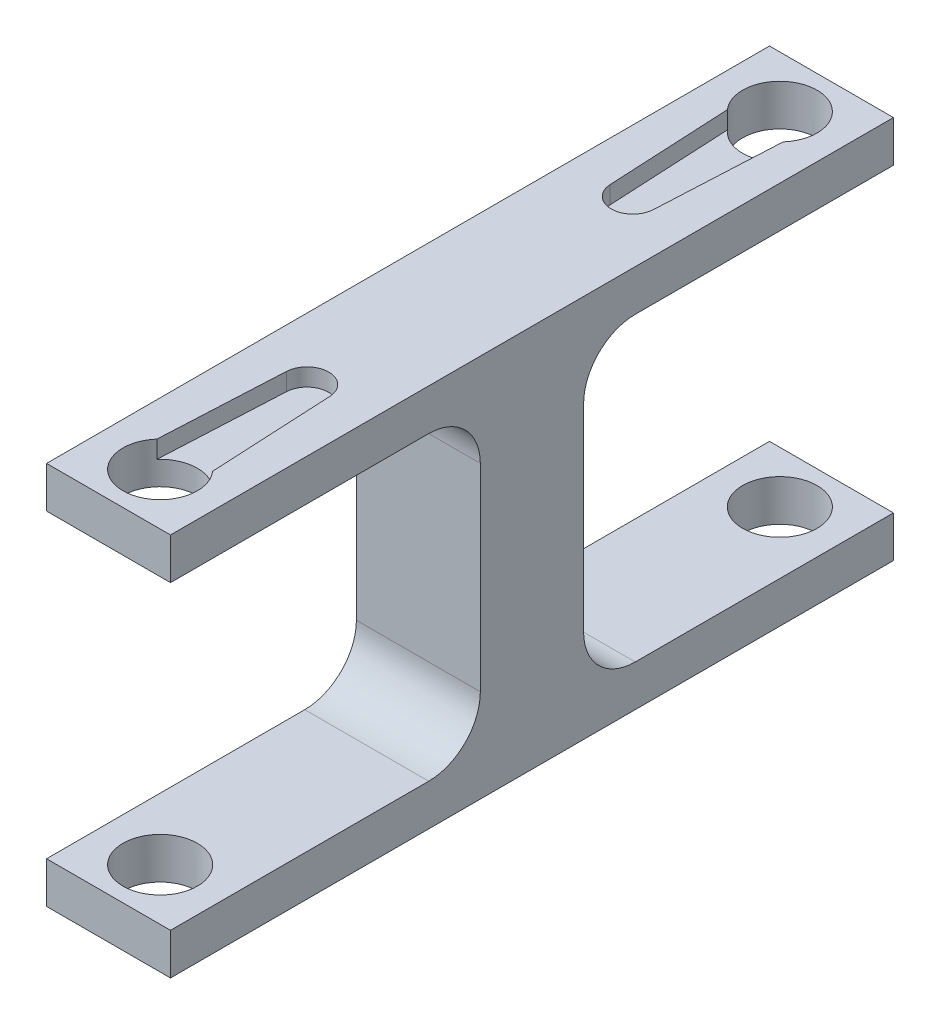
SolidWorks part; units mm, degrees
ref_plane "Front Plane" through (0, 0, 0) normal (0, 0, 1) x (1, 0, 0)
ref_plane "Top Plane" through (0, 0, 0) normal (0, 1, 0) x (1, 0, 0)
ref_plane "Right Plane" through (0, 0, 0) normal (1, 0, 0) x (0, 0, -1)
sketch "Sketch2" plane through (0, 0, 0) normal (0, 0, 1) x (1, 0, 0)
  line L1 (-8.6116, 0.9665) -> (3.3884, 0.9665)
  line L2 (-8.6116, 0.9665) -> (-8.6116, -36.1835)
  line L3 (-8.6116, -36.1835) -> (3.3884, -36.1835)
  line L4 (3.3884, 0.9665) -> (3.3884, -36.1835)
  dimension "D1" = 12
  dimension "D2" = 37.15
extrude "Boss-Extrude2" add sketch "Sketch2" along normal blind 2.5
sketch "Sketch11" plane through (0, 0, 2.5) normal (0, 0, 1) x (1, 0, 0)
  line L0 (3.3884, 0.9665) -> (3.3884, -36.1835) construction
  line L1 (-8.6116, 0.9665) -> (3.3884, 0.9665)
  line L2 (-8.6116, 0.9665) -> (-8.6116, -3.0335)
  line L3 (-8.6116, -3.0335) -> (3.3884, -3.0335)
  line L4 (3.3884, 0.9665) -> (3.3884, -3.0335)
  line L6 (-8.6116, -36.1835) -> (3.3884, -36.1835)
  line L7 (-8.6116, -36.1835) -> (-8.6116, -32.1835)
  line L8 (-8.6116, -32.1835) -> (3.3884, -32.1835)
  line L9 (3.3884, -36.1835) -> (3.3884, -32.1835)
  dimension "D1" = 4
  dimension "D2" = 4
extrude "Boss-Extrude8" add sketch "Sketch11" along normal blind 30
sketch "Sketch12" plane through (0, 0.9665, 0) normal (0, 1, 0) x (1, 0, 0)
  line L2 (-0.5143, -13.1688) -> (0.0884, -25.1188)
  line L6 (-5.3116, -25.1188) -> (-4.7089, -13.1688)
  line L7 (3.3884, -32.5) -> (-8.6116, -32.5) construction
  line L8 (-2.6116, -27.5) -> (-2.6116, -32.5) construction
  arc A4 (-5.3116, -25.1188) -> (0.0884, -25.1188) centre (-2.6116, -27.5) ccw
  arc A5 (-0.5143, -13.1688) -> (-4.7089, -13.1688) centre (-2.6116, -13.2745) ccw
  dimension "D1" = 3.6
  dimension "D5" = 2.1
  dimension "D2" = 5
  dimension "D3" = 11.95
  dimension "D4" = 11.95
  dimension "D6" = 5.4
extrude "Cut-Extrude1" cut sketch "Sketch12" against normal blind 1.7
sketch "Sketch14" plane through (0, 0, 0) normal (0, 0, -1) x (-1, 0, 0)
  line L9 (-3.3884, 0.9665) -> (8.6116, 0.9665)
  line L10 (-3.3884, 0.9665) -> (-3.3884, -36.1835)
  line L11 (-3.3884, -36.1835) -> (8.6116, -36.1835)
  line L12 (8.6116, 0.9665) -> (8.6116, -36.1835)
extrude "Boss-Extrude9" add sketch "Sketch14" along normal blind 7.5
sketch "Sketch16" plane through (0, 0, -7.5) normal (0, 0, -1) x (-1, 0, 0)
  line L0 (8.6116, -36.1835) -> (8.6116, 0.9665) construction
  line L1 (-3.3884, 0.9665) -> (8.6116, 0.9665)
  line L2 (-3.3884, 0.9665) -> (-3.3884, -3.0335)
  line L3 (-3.3884, -3.0335) -> (8.6116, -3.0335)
  line L4 (8.6116, 0.9665) -> (8.6116, -3.0335)
  line L6 (-3.3884, -36.1835) -> (8.6116, -36.1835)
  line L7 (-3.3884, -36.1835) -> (-3.3884, -32.1835)
  line L8 (-3.3884, -32.1835) -> (8.6116, -32.1835)
  line L9 (8.6116, -36.1835) -> (8.6116, -32.1835)
  dimension "D1" = 4
  dimension "D2" = 4
extrude "Boss-Extrude11" add sketch "Sketch16" along normal blind 30
sketch "Sketch20" plane through (0, 0.9665, 0) normal (0, 1, 0) x (1, 0, 0)
  line L4 (-4.7089, 18.1688) -> (-5.3116, 30.1188)
  line L8 (0.0884, 30.1188) -> (-0.5143, 18.1688)
  line L9 (-8.6116, 37.5) -> (3.3884, 37.5) construction
  line L10 (-2.6116, 32.5) -> (-2.6116, 37.5) construction
  arc A6 (0.0884, 30.1188) -> (-5.3116, 30.1188) centre (-2.6116, 32.5) ccw
  arc A7 (-4.7089, 18.1688) -> (-0.5143, 18.1688) centre (-2.6116, 18.2745) ccw
  dimension "D1" = 3.6
  dimension "D5" = 2.1
  dimension "D2" = 5
  dimension "D3" = 11.95
  dimension "D4" = 11.95
  dimension "D6" = 5.4
extrude "Cut-Extrude4" cut sketch "Sketch20" against normal blind 1.7
sketch "Sketch22" plane through (0, 0.9665, 0) normal (0, 1, 0) x (1, 0, 0)
  circle A0 centre (-2.6116, -27.5) radius 3.6
  dimension "D1" = 7.2
extrude "Cut-Extrude6" cut sketch "Sketch22" against normal through all
sketch "Sketch23" plane through (0, 0.9665, 0) normal (0, 1, 0) x (1, 0, 0)
  circle A0 centre (-2.6116, 32.5) radius 3.6
  dimension "D1" = 7.2
extrude "Cut-Extrude7" cut sketch "Sketch23" against normal through all
fillet "Fillet1" radius 5 1 edges at (-2.6116, -3.0335, 2.5)
fillet "Fillet2" radius 5 1 edges at (-2.6116, -32.1835, 2.5)
fillet "Fillet3" radius 5 1 edges at (-2.6116, -3.0335, -7.5)
fillet "Fillet4" radius 5 1 edges at (-2.6116, -32.1835, -7.5)
